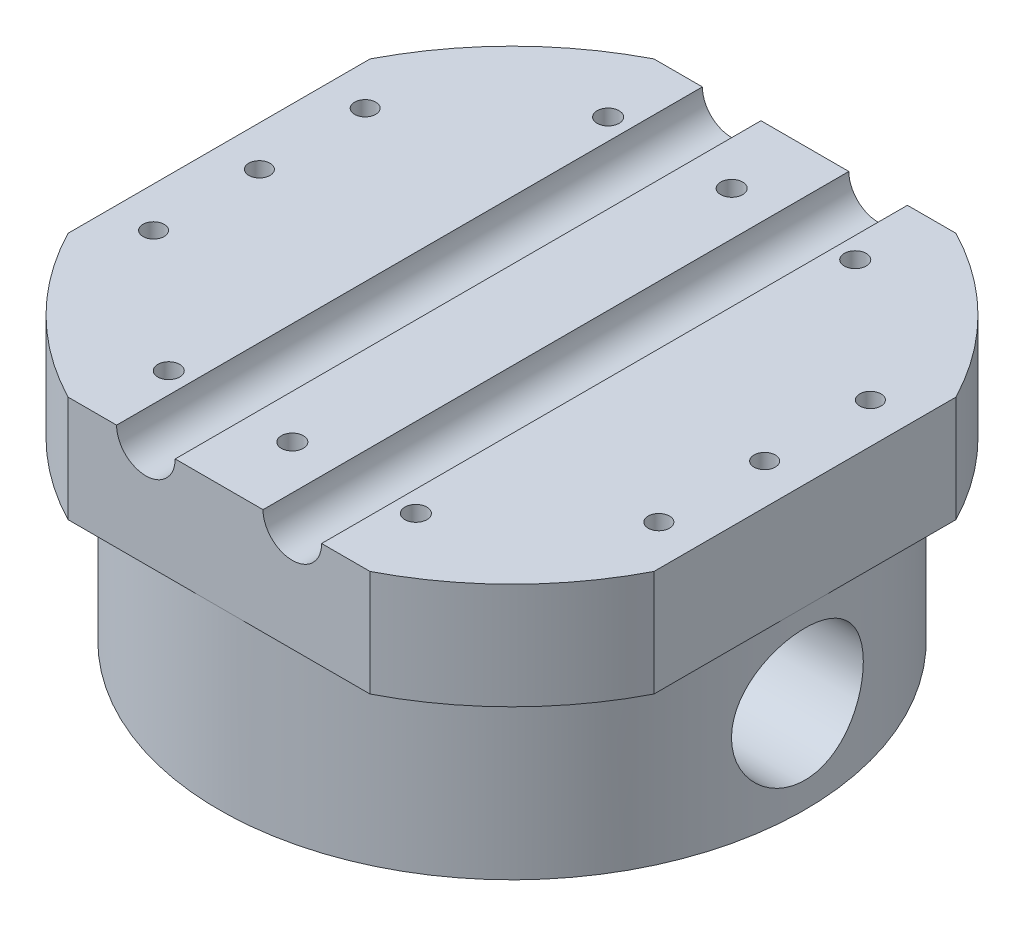
SolidWorks part; units mm, degrees
ref_plane "Alzado" through (0, 0, 0) normal (0, 0, 1) x (1, 0, 0)
ref_plane "Planta" through (0, 0, 0) normal (0, 1, 0) x (1, 0, 0)
ref_plane "Vista lateral" through (0, 0, 0) normal (1, 0, 0) x (0, 0, -1)
sketch "Croquis1" plane through (0, 0, 0) normal (0, 1, 0) x (1, 0, 0)
  line L0 (0, -45) -> (0, -40) construction
  line L1 (-45, 0) -> (-40, 0) construction
  line L2 (0, 45) -> (0, 40) construction
  line L3 (45, 0) -> (40, 0) construction
  line L5 (-40, -40) -> (40, -40)
  line L6 (-40, -40) -> (-40, 40)
  line L7 (-40, 40) -> (40, 40)
  line L8 (40, -40) -> (40, 40)
  line L9 (-40, -40) -> (40, 40) construction
  line L10 (-40, 40) -> (40, -40) construction
  circle A0 centre (0, 0) radius 45
extrude "Saliente-Extruir1" add sketch "Croquis1" along normal blind 40 contours L5 A0 L8 L7 L6
sketch "Croquis5" plane through (0, 40, 0) normal (0, 1, 0) x (1, 0, 0)
  line L0 (-40, 0) -> (-29, 0) construction
  line L1 (-40, -20.6155) -> (-40, 20.6155) construction
  line L2 (-34.5, 0) -> (-34.5, 28.892) construction
  line L3 (-34.5, 0) -> (-34.5, -28.892) construction
  arc A0 (-20.6155, 40) -> (-40, 20.6155) centre (0, 0) ccw construction
  arc A1 (-40, -20.6155) -> (-20.6155, -40) centre (0, 0) ccw construction
  circle A2 centre (-34.5, 14.446) radius 1.45
  circle A3 centre (-34.5, -14.446) radius 1.45
  circle A4 centre (-34.5, 0) radius 1.45
extrude "Cortar-Extruir3" cut sketch "Croquis5" against normal blind 15
mirror "Simetría1" about plane through (0, 0, 0) normal (1, 0, 0) of "Cortar-Extruir3"
sketch "Croquis6" plane through (0, 0, 40) normal (0, 0, 1) x (1, 0, 0)
  line L0 (0, 40) -> (10, 40) construction
  line L1 (-20.6155, 40) -> (20.6155, 40) construction
  line L2 (0, 40) -> (-10, 40) construction
  circle A0 centre (-10, 40) radius 4
  circle A1 centre (10, 40) radius 4
extrude "Cortar-Extruir4" cut sketch "Croquis6" against normal blind 106
sketch "Croquis8" plane through (0, 0, 0) normal (0, -1, 0) x (1, 0, 0)
  circle A0 centre (0, 0) radius 10.1
extrude "Cortar-Extruir5" cut sketch "Croquis8" against normal blind 27
sketch "Croquis9" plane through (-40, 0, 0) normal (-1, 0, 0) x (0, 0, 1)
  line L0 (0, 0) -> (0, 10.4) construction
  line L1 (20.6155, 0) -> (-20.6155, 0) construction
  line L2 (0, 10.4) -> (0, 14) construction
  circle A0 centre (0, 14) radius 3.75
extrude "Cortar-Extruir6" cut sketch "Croquis9" against normal blind 80
sketch "Croquis12" plane through (0, 40, 0) normal (0, 1, 0) x (1, 0, 0)
  line L0 (0, -40) -> (0, -30) construction
  line L1 (-6, -40) -> (6, -40) construction
  line L2 (0, -30) -> (16.875, -30) construction
  line L3 (0, -30) -> (-16.875, -30) construction
  line L4 (0, 40) -> (0, 30) construction
  line L5 (-6, 40) -> (6, 40) construction
  line L6 (0, 30) -> (-16.875, 30) construction
  line L7 (0, 30) -> (16.875, 30) construction
  circle A0 centre (-16.875, 30) radius 1.5
  circle A1 centre (0, 30) radius 1.5
  circle A2 centre (16.875, 30) radius 1.5
  circle A3 centre (-16.875, -30) radius 1.5
  circle A4 centre (0, -30) radius 1.5
  circle A5 centre (16.875, -30) radius 1.5
extrude "Cortar-Extruir8" cut sketch "Croquis12" against normal blind 15
sketch "Croquis16" plane through (40, 0, 0) normal (1, 0, 0) x (0, 0, -1)
  line L0 (0, 0) -> (0, 3) construction
  line L1 (-40, 40) -> (-40, 0) construction
  line L2 (-40, 3) -> (40, 3)
  line L3 (-40, 3) -> (-40, 0)
  line L4 (-40, 0) -> (40, 0)
  line L5 (40, 3) -> (40, 0)
extrude "Cortar-Extruir11" cut sketch "Croquis16" against normal blind 80
sketch "Croquis21" plane through (0, 3, 0) normal (0, -1, 0) x (1, 0, 0)
  circle A0 centre (0, 0) radius 22.4
  circle A1 centre (0, 0) radius 33
extrude "Cortar-Extruir12" cut sketch "Croquis21" against normal blind 1
sketch "Croquis22" plane through (0, 3, 0) normal (0, -1, 0) x (1, 0, 0)
  circle A0 centre (0, 0) radius 22.4
extrude "Saliente-Extruir2" add sketch "Croquis22" along normal blind 2.5
sketch "Croquis24" plane through (0, 3, 0) normal (0, -1, 0) x (1, 0, 0)
  circle A0 centre (0, 0) radius 33
  circle A1 centre (0, 0) radius 40
extrude "Saliente-Extruir3" add sketch "Croquis24" along normal blind 1.5
sketch "Croquis25" plane through (0, 0.5, 0) normal (0, -1, 0) x (1, 0, 0)
  circle A0 centre (0, 0) radius 13
extrude "Cortar-Extruir13" cut sketch "Croquis25" against normal blind 7
sketch "Croquis26" plane through (40, 0, 0) normal (1, 0, 0) x (0, 0, -1)
  circle A0 centre (0, 14) radius 9
extrude "Cortar-Extruir14" cut sketch "Croquis26" against normal blind 24
sketch "Croquis27" plane through (-40, 0, 0) normal (-1, 0, 0) x (0, 0, 1)
  circle A0 centre (0, 14) radius 9
extrude "Cortar-Extruir15" cut sketch "Croquis27" against normal blind 25.5
sketch "Croquis28" plane through (0, 0.5, 0) normal (0, -1, 0) x (1, 0, 0)
  circle A0 centre (0, 0) radius 40
  circle A1 centre (0, 0) radius 45
extrude "Cortar-Extruir16" cut sketch "Croquis28" against normal blind 25
